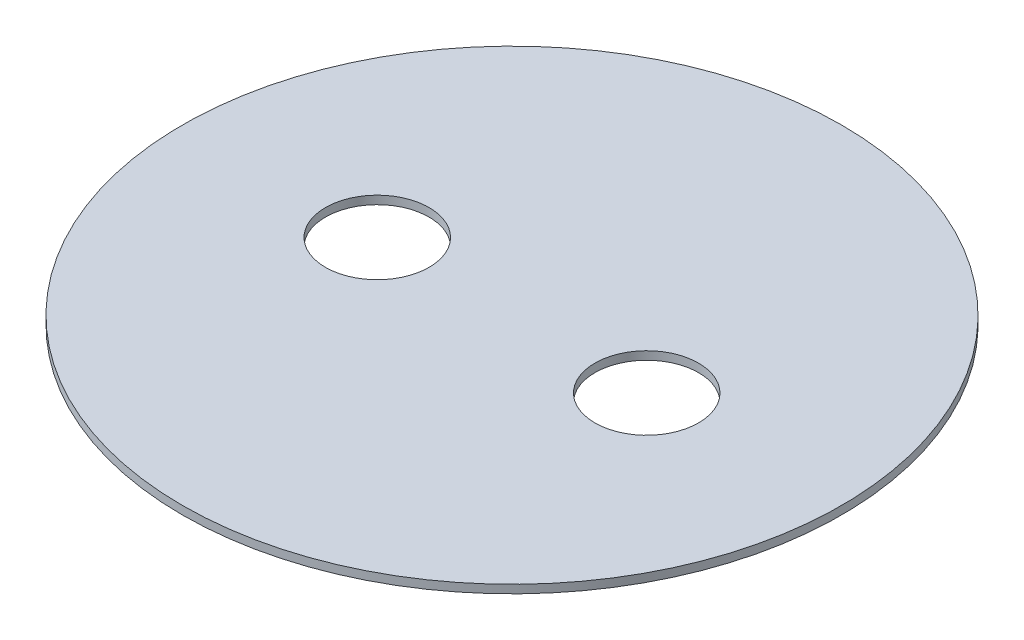
SolidWorks part; units mm, degrees
material "AÇO 1020"
ref_plane "Front Plane" through (0, 0, 0) normal (0, 0, 1) x (1, 0, 0)
ref_plane "Top Plane" through (0, 0, 0) normal (0, 1, 0) x (1, 0, 0)
ref_plane "Right Plane" through (0, 0, 0) normal (1, 0, 0) x (0, 0, -1)
sketch "Sketch1" plane through (0, 0, 0) normal (0, 1, 0) x (1, 0, 0)
  line L0 (0, 0) -> (0, 79.5) construction
  circle A0 centre (0, 0) radius 79.5
  circle A1 centre (-32.5, 0) radius 12.5
  circle A2 centre (32.5, 0) radius 12.5
  dimension "D1" = 159
  dimension "D2" = 25
  dimension "D3" = 65
extrude "Extrude1" add sketch "Sketch1" along normal blind 2
